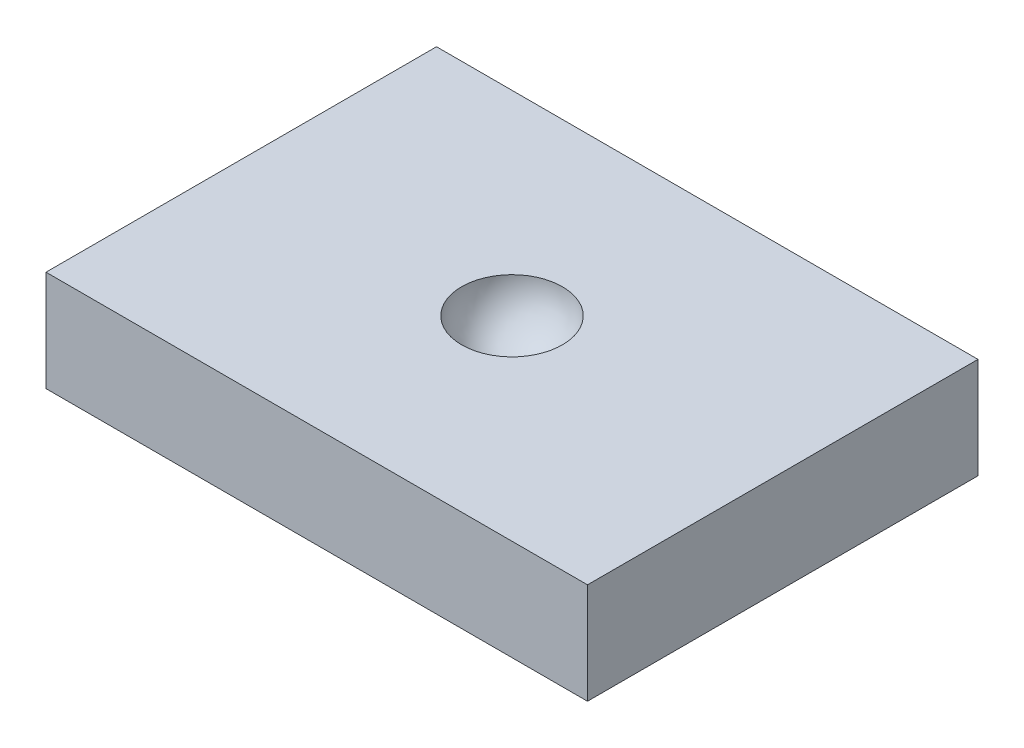
SolidWorks part; units mm, degrees
ref_plane "Plan de face" through (0, 0, 0) normal (0, 0, 1) x (1, 0, 0)
ref_plane "Plan de dessus" through (0, 0, 0) normal (0, 1, 0) x (1, 0, 0)
ref_plane "Plan de droite" through (0, 0, 0) normal (1, 0, 0) x (0, 0, -1)
sketch "Esquisse1" plane through (0, 0, 0) normal (0, 1, 0) x (1, 0, 0)
  line L1 (0, 0) -> (-26.8471, 0)
  line L2 (0, 0) -> (0, 19.3609)
  line L3 (0, 19.3609) -> (-26.8471, 19.3609)
  line L4 (-26.8471, 0) -> (-26.8471, 19.3609)
extrude "Boss.-Extru.1" add sketch "Esquisse1" along normal blind 5
sketch "Esquisse2" plane through (0, 5, 0) normal (0, 1, 0) x (1, 0, 0)
  line L0 (-13.4236, 12.1781) -> (-13.4236, 7.1828)
  line L1 (-13.4236, 17.2602) -> (-13.4236, 3.1296) construction
  arc A0 (-13.4236, 7.1828) -> (-13.4236, 12.1781) centre (-13.4236, 9.6805) ccw
revolve "Enlèvement de matière-Révolution1" cut sketch "Esquisse2" angle 360 about L1
